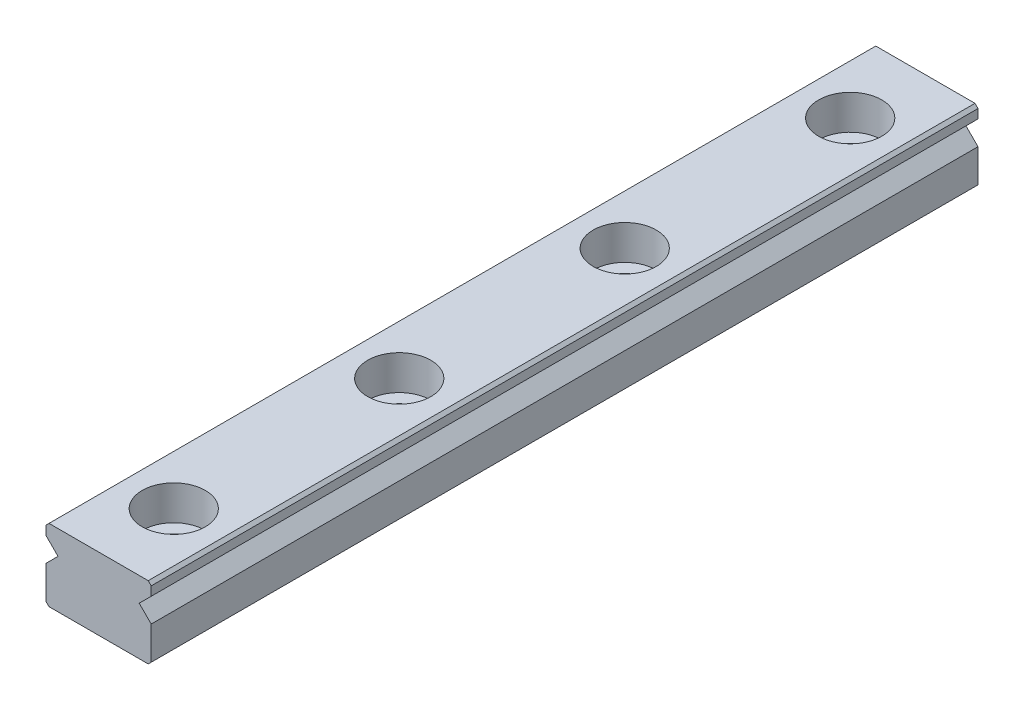
SolidWorks part; units mm, degrees
material "合金钢"
ref_plane "前视基准面" through (0, 0, 0) normal (0, 0, 1) x (1, 0, 0)
ref_plane "上视基准面" through (0, 0, 0) normal (0, 1, 0) x (1, 0, 0)
ref_plane "右视基准面" through (0, 0, 0) normal (1, 0, 0) x (0, 0, -1)
sketch "草图1" plane through (0, 0, 0) normal (0, 0, 1) x (1, 0, 0)
  line L0 (-3.5, 0) -> (3.5, 0)
  line L1 (3.5, 0) -> (3.5, 2.4)
  line L2 (3.5, 2.4) -> (2.7, 3.2)
  line L3 (2.7, 3.2) -> (3.5, 4)
  line L4 (3.5, 4) -> (3.5, 4.8)
  line L5 (3.5, 4.8) -> (-3.5, 4.8)
  line L6 (-3.5, 4.8) -> (-3.5, 4)
  line L7 (-3.5, 4) -> (-2.7, 3.2)
  line L8 (-2.7, 3.2) -> (-3.5, 2.4)
  line L9 (-3.5, 2.4) -> (-3.5, 0)
  line L10 (0, 4.8) -> (0, 0) construction
  dimension "D1" = 7
  dimension "D2" = 4.8
  dimension "D3" = 0.8
  dimension "D4" = 0.8
extrude "凸台-拉伸1" add sketch "草图1" along normal blind 55
sketch "草图2" plane through (0, 4.8, 0) normal (0, 1, 0) x (1, 0, 0)
  line L0 (-3.5, -27.5) -> (3.5, -27.5) construction
  line L1 (-3.5, -55) -> (-3.5, 0) construction
  line L2 (3.5, -55) -> (3.5, 0) construction
  circle A0 centre (0, -5) radius 2.1
  circle A1 centre (0, -20) radius 2.1
  circle A2 centre (0, -35) radius 2.1
  circle A3 centre (0, -50) radius 2.1
  point P16 (0, -27.5)
  dimension "D1" = 4.2
  dimension "D2" = 15
  dimension "D3" = 15
extrude "切除-拉伸1" cut sketch "草图2" against normal blind 2.3
chamfer "倒角1" distance 0.2 angle 45 4 edges at (-3.5, 0, 27.5) (-3.5, 4.8, 27.5) (3.5, 0, 27.5) (3.5, 4.8, 27.5)
sketch "草图4" plane through (0, 2.5, 0) normal (0, 1, 0) x (1, 0, 0)
  circle A0 centre (0, -5) radius 1.2
  circle A1 centre (0, -20) radius 1.2
  circle A2 centre (0, -50) radius 1.2
  circle A3 centre (0, -35) radius 1.2
  dimension "D1" = 2.4
extrude "切除-拉伸3" cut sketch "草图4" against normal through all
